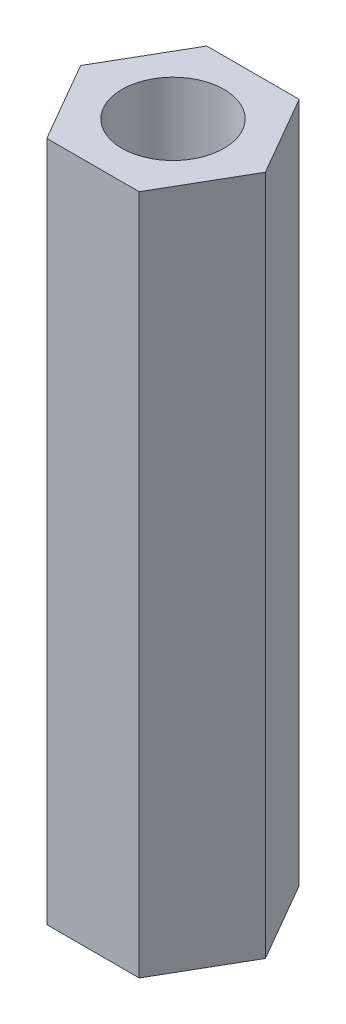
SolidWorks part; units mm, degrees
ref_plane "前视基准面" through (0, 0, 0) normal (0, 0, 1) x (1, 0, 0)
ref_plane "上视基准面" through (0, 0, 0) normal (0, 1, 0) x (1, 0, 0)
ref_plane "右视基准面" through (0, 0, 0) normal (1, 0, 0) x (0, 0, -1)
sketch "草图2" plane through (0, 0, 0) normal (0, 1, 0) x (1, 0, 0)
  line L1 (1.3568, -2.35) -> (2.7135, 0)
  line L2 (2.7135, 0) -> (1.3568, 2.35)
  line L3 (1.3568, 2.35) -> (-1.3568, 2.35)
  line L4 (-1.3568, 2.35) -> (-2.7135, 0)
  line L5 (-2.7135, 0) -> (-1.3568, -2.35)
  line L6 (-1.3568, -2.35) -> (1.3568, -2.35)
  circle A0 centre (0, 0) radius 2.35 construction
  circle A1 centre (0, 0) radius 1.5
  dimension "D1" = 4.7
extrude "凸台-拉伸1" add sketch "草图2" along normal blind 20
